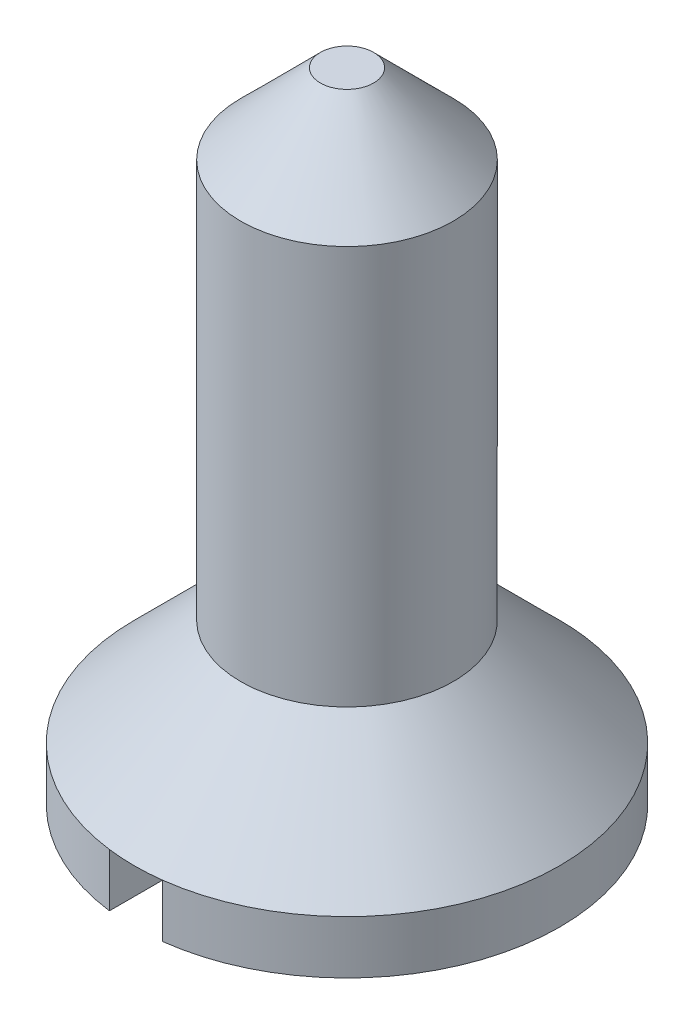
SolidWorks part; units mm, degrees
ref_plane "Спереди" through (0, 0, 0) normal (0, 0, 1) x (1, 0, 0)
ref_plane "Сверху" through (0, 0, 0) normal (0, 1, 0) x (1, 0, 0)
ref_plane "Справа" through (0, 0, 0) normal (1, 0, 0) x (0, 0, -1)
sketch "Эскиз1" plane through (0, 0, 0) normal (0, 0, 1) x (1, 0, 0)
  line L0 (0, 0) -> (-4, 0)
  line L1 (-4, 0) -> (-4, 1)
  line L2 (-4, 1) -> (-2, 3)
  line L3 (-2, 3) -> (-2, 12)
  line L4 (-2, 12) -> (0, 12)
  line L5 (0, 12) -> (0, 0)
  line L6 (-2, 3) -> (0, 3) construction
  dimension "D1" = 12
  dimension "D2" = 4
  dimension "D3" = 2
  dimension "D4" = 45
  dimension "D5" = 3
revolve "Повернуть1" add sketch "Эскиз1" angle 360 about L5
sketch "Эскиз2" plane through (0, 0, 0) normal (0, 0, 1) x (1, 0, 0)
  line L0 (-4, 0) -> (4, 0) construction
  line L1 (-0.5, 0) -> (0.5, 0)
  line L2 (-0.5, 0) -> (-0.5, 1)
  line L3 (-0.5, 1) -> (0.5, 1)
  line L4 (0.5, 0) -> (0.5, 1)
  dimension "D1" = 1
  dimension "D2" = 1
extrude "Вырез-Вытянуть1" cut sketch "Эскиз2" against normal mid plane 20
chamfer "Фаска1" distance 1.5 angle 45 1 edges at (-2, 12, 0)
